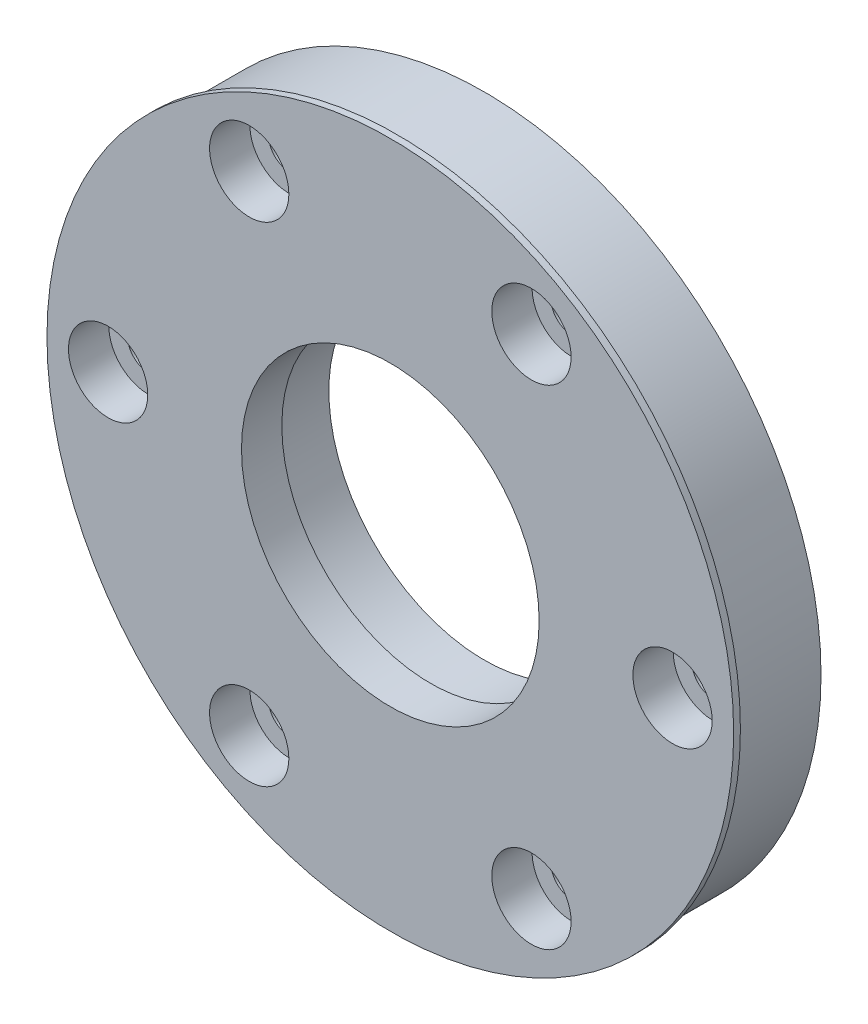
SolidWorks part; units mm, degrees
material "ABS"
ref_plane "Front Plane" through (0, 0, 0) normal (0, 0, 1) x (1, 0, 0)
ref_plane "Top Plane" through (0, 0, 0) normal (0, 1, 0) x (1, 0, 0)
ref_plane "Right Plane" through (0, 0, 0) normal (1, 0, 0) x (0, 0, -1)
sketch "Output Master Sketch" plane through (0, 0, 0) normal (0, 0, 1) x (1, 0, 0)
  circle A0 centre (0, 0) radius 21 construction
  circle A1 centre (21, 0) radius 2.95 construction
  circle A2 centre (10.5, -18.1865) radius 2.95 construction
  circle A3 centre (-10.5, -18.1865) radius 2.95 construction
  circle A4 centre (-21, 0) radius 2.95 construction
  circle A5 centre (-10.5, 18.1865) radius 2.95 construction
  circle A6 centre (10.5, 18.1865) radius 2.95 construction
  circle A7 centre (0, 0) radius 25.05
  point P17 (0, 0)
sketch "Sketch2" plane through (0, 0, 0) normal (0, 0, 1) x (1, 0, 0)
  circle A0 centre (0, 0) radius 25.05
  circle A1 centre (0, 0) radius 25.05 construction
extrude "Boss-Extrude1" add sketch "Sketch2" along normal blind 7
sketch "Sketch3" plane through (0, 0, 7) normal (0, 0, 1) x (1, 0, 0)
  circle A0 centre (-21, 0) radius 2.95
  circle A1 centre (-21, 0) radius 2.95 construction
  circle A2 centre (-10.5, 18.1865) radius 2.95
  circle A3 centre (10.5, 18.1865) radius 2.95
  circle A4 centre (21, 0) radius 2.95
  circle A5 centre (10.5, -18.1865) radius 2.95
  circle A6 centre (-10.5, -18.1865) radius 2.95
  point P18 (0, 0)
  dimension "D1" = 5.9
  dimension "D2" = 6
extrude "Dowel Pin Cutout" cut sketch "Sketch3" against normal blind 3
sketch "Sketch4" plane through (0, 0, 7) normal (0, 0, 1) x (1, 0, 0)
  circle A0 centre (0, 0) radius 25.05
  circle A1 centre (0, 0) radius 25.55
  circle A3 centre (0, 0) radius 25.05 construction
  dimension "D1" = 0.5
extrude "Main Housing Bearing Retainer" add sketch "Sketch4" against normal blind 0.5
sketch "Sketch5" plane through (0, 0, 0) normal (0, 0, -1) x (-1, 0, 0)
  circle A0 centre (-21, 0) radius 1.55
  circle A1 centre (-10.5, 18.1865) radius 1.55
  circle A2 centre (10.5, 18.1865) radius 1.55
  circle A3 centre (21, 0) radius 1.55
  circle A4 centre (10.5, -18.1865) radius 1.55
  circle A5 centre (-10.5, -18.1865) radius 1.55
  point P15 (0, 0)
  dimension "D1" = 3.1
  dimension "D2" = 6
extrude "M3 Thru" cut sketch "Sketch5" against normal through all
sketch "Sketch6" plane through (0, 0, 0) normal (0, 0, -1) x (-1, 0, 0)
  circle A0 centre (-21, 0) radius 3
  circle A1 centre (-10.5, 18.1865) radius 3
  circle A2 centre (10.5, 18.1865) radius 3
  circle A3 centre (21, 0) radius 3
  circle A4 centre (10.5, -18.1865) radius 3
  circle A5 centre (-10.5, -18.1865) radius 3
  point P15 (0, 0)
  dimension "D1" = 6
  dimension "D2" = 6
extrude "M3 Button Head Cutout" cut sketch "Sketch6" against normal blind 1.7
sketch "Sketch8" plane through (0, 0, 7) normal (0, 0, 1) x (1, 0, 0)
  circle A0 centre (0, 0) radius 11.575
  dimension "D1" = 23.15
extrude "Input Shaft Bearing Cutout" cut sketch "Sketch8" against normal through all
sketch "Sketch9" plane through (0, 0, 0) normal (0, 0, -1) x (-1, 0, 0)
  circle A0 centre (0, 0) radius 11.575
  circle A1 centre (0, 0) radius 11.075
  circle A2 centre (0, 0) radius 11.575 construction
  dimension "D1" = 0.5
extrude "Input Shaft Bearing Retainer" add sketch "Sketch9" along normal blind 3 from surface at -7 starting at face at (11.575, 0, 7)
